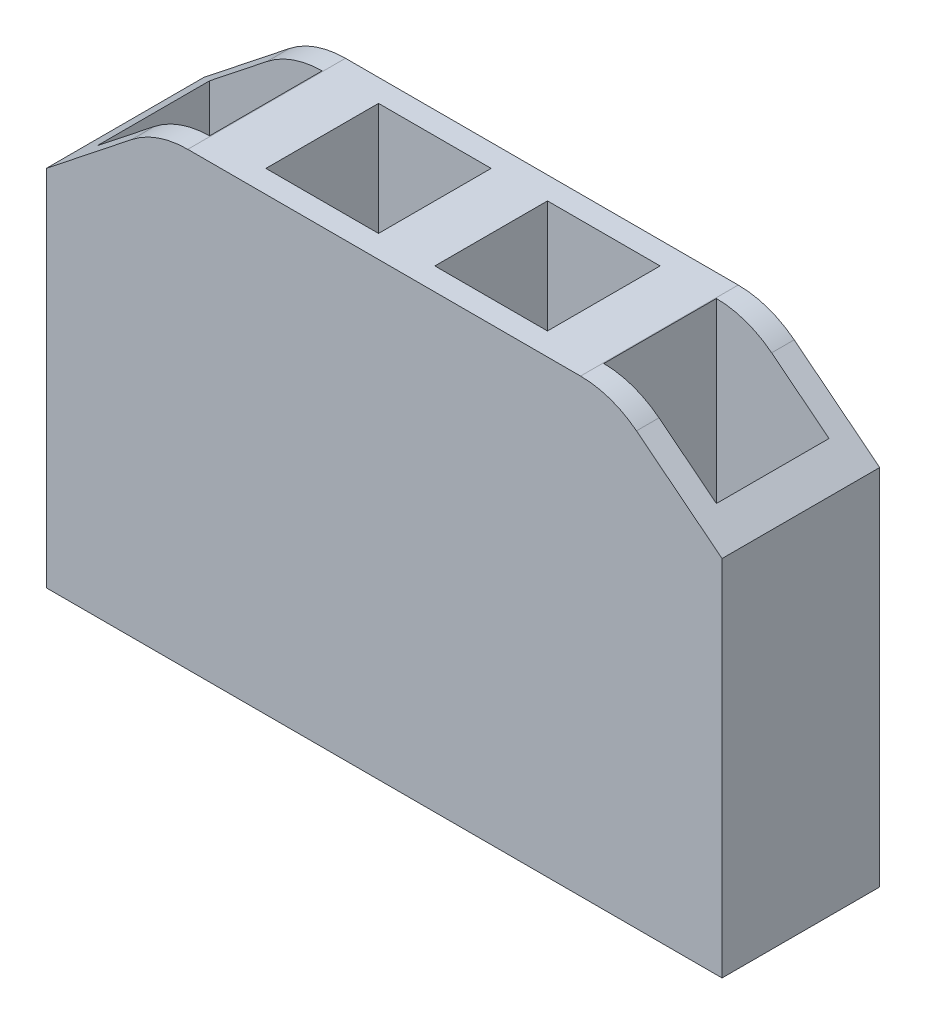
SolidWorks part; units mm, degrees
ref_plane "Front Plane" through (0, 0, 0) normal (0, 0, 1) x (1, 0, 0)
ref_plane "Top Plane" through (0, 0, 0) normal (0, 1, 0) x (1, 0, 0)
ref_plane "Right Plane" through (0, 0, 0) normal (1, 0, 0) x (0, 0, -1)
sketch "Sketch1" plane through (0, 0, 0) normal (0, 1, 0) x (1, 0, 0)
  line L1 (-7.5, 1.75) -> (7.5, 1.75)
  line L2 (-7.5, 1.75) -> (-7.5, -1.75)
  line L3 (-7.5, -1.75) -> (7.5, -1.75)
  line L4 (7.5, 1.75) -> (7.5, -1.75)
  line L5 (-7.5, 1.75) -> (7.5, -1.75) construction
  line L6 (-7.5, -1.75) -> (7.5, 1.75) construction
  point P0 (0, 0)
  dimension "D1" = 15
  dimension "D2" = 3.5
extrude "Boss-Extrude1" add sketch "Sketch1" along normal blind 10
sketch "Sketch2" plane through (0, 0, 1.75) normal (0, 0, 1) x (1, 0, 0)
  line L0 (-7.5, 8.0632) -> (-5.055, 10)
  line L1 (-7.5, 10) -> (-7.5, 0) construction
  line L2 (-7.5, 10) -> (7.5, 10) construction
  line L3 (-5.055, 10) -> (5.055, 10)
  line L4 (0, 10) -> (0, 11.0397) construction
  line L5 (7.5, 8.0632) -> (5.055, 10)
extrude "Cut-Extrude1" cut sketch "Sketch2" against normal through all and the other way through all flip side to cut
fillet "Fillet1" radius 2 2 edges at (5.055, 10, 0) (-5.055, 10, 0)
sketch "Sketch3" plane through (0, 10, 0) normal (0, 1, 0) x (1, 0, 0)
  line L0 (0, 0) -> (0, 3.0383) construction
  line L1 (-7.5, -1.75) -> (-7.5, 1.75) construction
  line L2 (-3.125, 1.25) -> (-0.625, 1.25)
  line L3 (-3.125, 1.25) -> (-3.125, -1.25)
  line L4 (-3.125, -1.25) -> (-0.625, -1.25)
  line L5 (-0.625, 1.25) -> (-0.625, -1.25)
  line L6 (-3.125, 1.25) -> (-0.625, -1.25) construction
  line L7 (-3.125, -1.25) -> (-0.625, 1.25) construction
  line L8 (-6.875, 1.25) -> (-4.375, 1.25)
  line L9 (-6.875, 1.25) -> (-6.875, -1.25)
  line L10 (-6.875, -1.25) -> (-4.375, -1.25)
  line L11 (-4.375, 1.25) -> (-4.375, -1.25)
  line L12 (-6.875, 1.25) -> (-4.375, -1.25) construction
  line L13 (-6.875, -1.25) -> (-4.375, 1.25) construction
  line L14 (6.875, -1.25) -> (4.375, 1.25) construction
  line L15 (6.875, 1.25) -> (4.375, -1.25) construction
  line L16 (3.125, -1.25) -> (0.625, 1.25) construction
  line L17 (3.125, 1.25) -> (0.625, -1.25) construction
  line L18 (4.375, 1.25) -> (4.375, -1.25)
  line L19 (6.875, -1.25) -> (4.375, -1.25)
  line L20 (6.875, 1.25) -> (6.875, -1.25)
  line L21 (6.875, 1.25) -> (4.375, 1.25)
  line L22 (0.625, 1.25) -> (0.625, -1.25)
  line L23 (3.125, -1.25) -> (0.625, -1.25)
  line L24 (3.125, 1.25) -> (3.125, -1.25)
  line L25 (3.125, 1.25) -> (0.625, 1.25)
  point P3 (-1.875, 0)
  point P8 (-5.625, 0)
  point P23 (5.625, 0)
  point P24 (1.875, 0)
  dimension "D1" = 0.625
  dimension "D2" = 2.5
  dimension "D3" = 2.5
  dimension "D4" = 0.625
  dimension "D5" = 2.5
  dimension "D6" = 2.5
extrude "Cut-Extrude2" cut sketch "Sketch3" against normal blind 8
